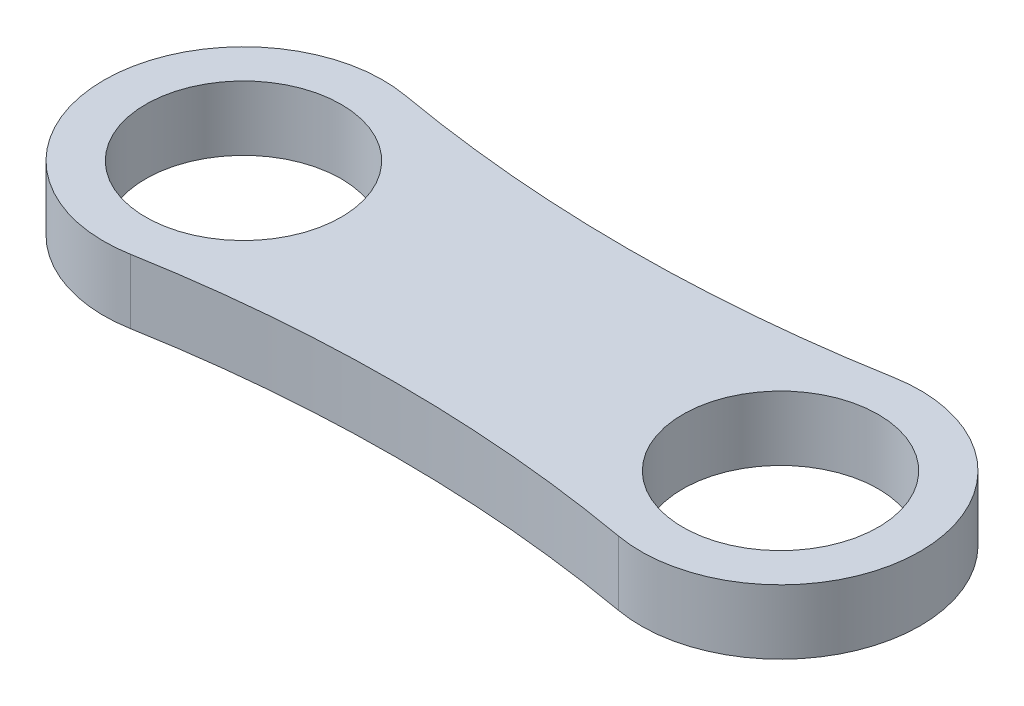
SolidWorks part; units mm, degrees
ref_plane "Front Plane" through (0, 0, 0) normal (0, 0, 1) x (1, 0, 0)
ref_plane "Top Plane" through (0, 0, 0) normal (0, 1, 0) x (1, 0, 0)
ref_plane "Right Plane" through (0, 0, 0) normal (1, 0, 0) x (0, 0, -1)
sketch "Sketch3" plane through (0, 0, 0) normal (0, 1, 0) x (1, 0, 0)
  line L0 (-3.175, 0) -> (3.175, 0) construction
  arc A0 (-2.8864, 1.6256) -> (-2.8864, -1.6256) centre (-3.175, 0) ccw
  arc A1 (2.8864, -1.6256) -> (2.8864, 1.6256) centre (3.175, 0) ccw
  arc A2 (-2.8864, 1.6256) -> (2.8864, 1.6256) centre (0, 17.8813) ccw
  arc A3 (2.8864, -1.6256) -> (-2.8864, -1.6256) centre (0, -17.8813) ccw
  circle A4 centre (-3.175, 0) radius 1.1557
  circle A5 centre (3.175, 0) radius 1.1557
  point P2 (0, 0)
  dimension "D2" = 3.302
  dimension "D3" = 16.51
  dimension "D4" = 2.3114
  dimension "D1" = 6.35
extrude "Boss-Extrude1" add sketch "Sketch3" along normal blind 0.762
